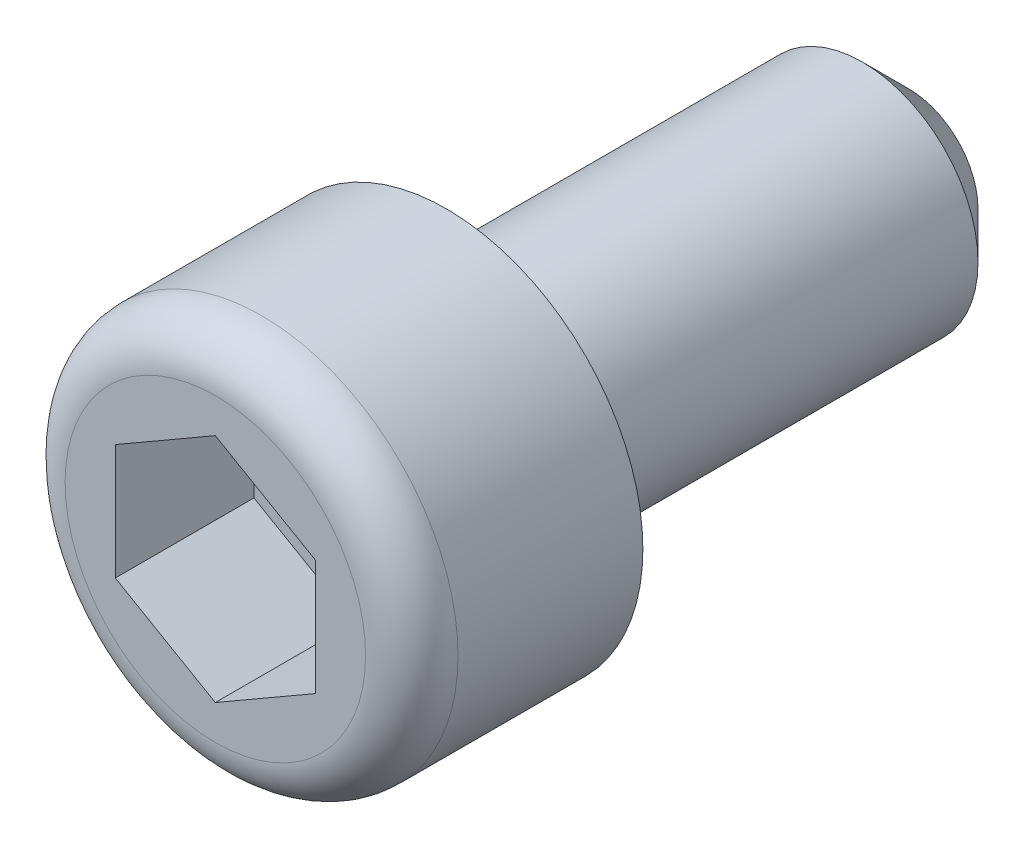
SolidWorks part; units mm, degrees
ref_plane "Front Plane" through (0, 0, 0) normal (0, 0, 1) x (1, 0, 0)
ref_plane "Top Plane" through (0, 0, 0) normal (0, 1, 0) x (1, 0, 0)
ref_plane "Right Plane" through (0, 0, 0) normal (1, 0, 0) x (0, 0, -1)
sketch "Sketch1" plane through (0, 0, 0) normal (1, 0, 0) x (0, 0, -1)
  line L0 (-156.2916, 0) -> (7658.2872, 0) construction
  line L1 (0, 0) -> (0, 4.25)
  line L2 (0, 4.25) -> (5, 4.25)
  line L3 (5, 4.25) -> (5, 2.5)
  line L4 (5, 2.5) -> (15, 2.5)
  line L5 (15, 2.5) -> (15, 0)
  line L6 (15, 0) -> (0, 0)
  dimension "D1" = 5
  dimension "D2" = 10
  dimension "D3" = 5
  dimension "D4" = 8.5
revolve "Body" add sketch "Sketch1" angle 360 about L0
sketch "Sketch2" plane through (0, 0, 0) normal (0, 0, 1) x (1, 0, 0)
  line L1 (0, 2.5) -> (-2.1651, 1.25)
  line L2 (-2.1651, 1.25) -> (-2.1651, -1.25)
  line L3 (-2.1651, -1.25) -> (0, -2.5)
  line L4 (0, -2.5) -> (2.1651, -1.25)
  line L5 (2.1651, -1.25) -> (2.1651, 1.25)
  line L6 (2.1651, 1.25) -> (0, 2.5)
  circle A0 centre (0, 0) radius 2.5 construction
  dimension "D1" = 5
extrude "Footprint" cut sketch "Sketch2" against normal blind 3
chamfer "Chamfer1" distance 1 angle 45 1 edges at (2.5, 0, -15)
fillet "Fillet1" radius 1 1 edges at (4.25, 0, 0)
